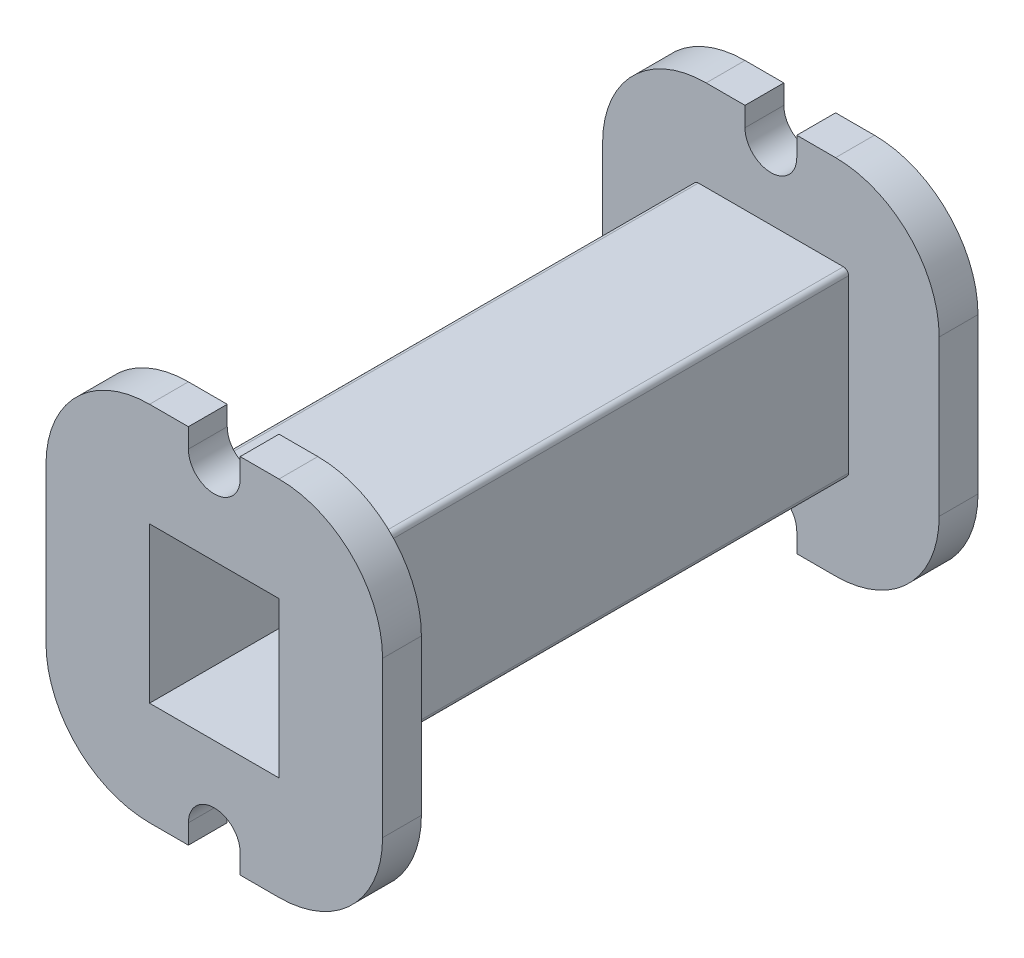
SolidWorks part; units mm, degrees
ref_plane "前视基准面" through (0, 0, 0) normal (0, 0, 1) x (1, 0, 0)
ref_plane "上视基准面" through (0, 0, 0) normal (0, 1, 0) x (1, 0, 0)
ref_plane "右视基准面" through (0, 0, 0) normal (1, 0, 0) x (0, 0, -1)
sketch "草图1" plane through (0, 0, 0) normal (0, 0, 1) x (1, 0, 0)
  line L0 (-3, 3.5) -> (3, 3.5)
  line L1 (-2.5, 3) -> (2.5, 3)
  line L2 (-2.5, 3) -> (-2.5, -3)
  line L3 (-2.5, -3) -> (2.5, -3)
  line L4 (2.5, 3) -> (2.5, -3)
  line L5 (-2.5, 3) -> (2.5, -3) construction
  line L6 (-2.5, -3) -> (2.5, 3) construction
  line L7 (3, 3.5) -> (3, -3.5)
  line L8 (-3, -3.5) -> (3, -3.5)
  line L9 (-3, 3.5) -> (-3, -3.5)
  point P0 (0, 0)
  dimension "D1" = 5
  dimension "D2" = 6
  dimension "D3" = 0.5
extrude "凸台-拉伸1" add sketch "草图1" along normal mid plane 23
sketch "草图2" plane through (0, 0, 11.5) normal (0, 0, 1) x (1, 0, 0)
  line L1 (-3, -3.5) -> (3, -3.5)
  line L2 (-3, -3.5) -> (-3, 3.5)
  line L3 (-3, 3.5) -> (3, 3.5)
  line L4 (3, -3.5) -> (3, 3.5)
  line L5 (-3, -3.5) -> (3, 3.5) construction
  line L6 (-3, 3.5) -> (3, -3.5) construction
  line L7 (-6.5, -10.75) -> (6.5, -10.75)
  line L8 (-6.5, -10.75) -> (-6.5, 10.75)
  line L9 (-6.5, 10.75) -> (6.5, 10.75)
  line L10 (6.5, -10.75) -> (6.5, 10.75)
  line L11 (-6.5, -10.75) -> (6.5, 10.75) construction
  line L12 (-6.5, 10.75) -> (6.5, -10.75) construction
  circle A0 centre (0, 0) radius 9.5
  point P0 (0, 0)
  point P7 (0, 0)
  line M3 (-3, 3.5) -> (-3, -3.5)
  line M4 (-3, -3.5) -> (3, -3.5)
  line M5 (3, -3.5) -> (3, 3.5)
  line M6 (3, 3.5) -> (-3, 3.5)
  dimension "D3" = 19
  dimension "D1" = 13
  dimension "D2" = 21.5
extrude "凸台-拉伸2" add sketch "草图2" against normal blind 1.5 contours L10 A0 L8 M3 M6 M5 M4
mirror "镜向1" about plane through (0, 0, 0) normal (0, 0, 1) of "凸台-拉伸2"
sketch "草图3" plane through (0, 0, 11.5) normal (0, 0, 1) x (1, 0, 0)
  line L1 (-9.3579, 7) -> (9.3579, 7)
  line L2 (-9.3579, 7) -> (-9.3579, -7)
  line L3 (-9.3579, -7) -> (9.3579, -7)
  line L4 (9.3579, 7) -> (9.3579, -7)
  line L5 (-9.3579, 7) -> (9.3579, -7) construction
  line L6 (-9.3579, -7) -> (9.3579, 7) construction
  circle A0 centre (0, 0) radius 19.1004
  point P0 (0, 0)
  dimension "D1" = 14
extrude "切除-拉伸1" cut sketch "草图3" against normal through all
sketch "草图4" plane through (0, 0, 11.5) normal (0, 0, 1) x (1, 0, 0)
  line L4 (-6.4226, -7) -> (6.4226, -7)
  line L5 (6.5, -6.9282) -> (6.5, 6.9282)
  line L6 (6.4226, 7) -> (-6.4226, 7)
  line L7 (-6.5, 6.9282) -> (-6.5, -6.9282)
  line L8 (-6.4226, -7) -> (6.4226, -7)
  line L9 (6.5, -6.9282) -> (6.5, 6.9282)
  line L10 (6.4226, 7) -> (-6.4226, 7)
  line L11 (-6.5, 6.9282) -> (-6.5, -6.9282)
  circle A0 centre (-2.5, 3) radius 4
  circle A1 centre (2.5, 3) radius 4
  circle A2 centre (2.5, -3) radius 4
  circle A3 centre (-2.5, -3) radius 4
  arc A8 (-6.5, -6.9282) -> (-6.4226, -7) centre (0, 0) ccw
  arc A9 (6.4226, -7) -> (6.5, -6.9282) centre (0, 0) ccw
  arc A10 (6.5, 6.9282) -> (6.4226, 7) centre (0, 0) ccw
  arc A11 (-6.4226, 7) -> (-6.5, 6.9282) centre (0, 0) ccw
  arc A12 (-6.5, -6.9282) -> (-6.4226, -7) centre (0, 0) ccw
  arc A13 (6.4226, -7) -> (6.5, -6.9282) centre (0, 0) ccw
  arc A14 (6.5, 6.9282) -> (6.4226, 7) centre (0, 0) ccw
  arc A15 (-6.4226, 7) -> (-6.5, 6.9282) centre (0, 0) ccw
  arc M17 (-6.5, -6.9282) -> (-6.4226, -7) centre (0, 0) ccw
  line M18 (-6.4226, -7) -> (6.4226, -7)
  arc M19 (6.4226, -7) -> (6.5, -6.9282) centre (0, 0) ccw
  line M20 (6.5, -6.9282) -> (6.5, 6.9282)
  arc M21 (6.5, 6.9282) -> (6.4226, 7) centre (0, 0) ccw
  line M22 (6.4226, 7) -> (-6.4226, 7)
  arc M23 (-6.4226, 7) -> (-6.5, 6.9282) centre (0, 0) ccw
  line M24 (-6.5, 6.9282) -> (-6.5, -6.9282)
  dimension "D1" = 0
extrude "切除-拉伸2" cut sketch "草图4" against normal through all contours A0 L10 M23 M24 | A1 L9 M21 M22 | A2 L8 M19 M20 | A3 M24 M17 M18
sketch "草图5" plane through (0, 0, 11.5) normal (0, 0, 1) x (1, 0, 0)
  line L0 (0, 7.75) -> (0, 6.25) construction
  line L1 (-6.2, 12.6435) -> (6.2, 12.6435)
  line L2 (-6.2, 12.6435) -> (-6.2, -12.6435)
  line L3 (-6.2, -12.6435) -> (6.2, -12.6435)
  line L4 (6.2, 12.6435) -> (6.2, -12.6435)
  line L5 (-6.2, 12.6435) -> (6.2, -12.6435) construction
  line L6 (-6.2, -12.6435) -> (6.2, 12.6435) construction
  line L7 (2.5, 7) -> (-2.5, 7) construction
  line L8 (1, 7.75) -> (1, 6.25)
  line L9 (-1, 7.75) -> (-1, 6.25)
  line L10 (0, -6.25) -> (0, -7.75) construction
  line L11 (-2.5, -7) -> (2.5, -7) construction
  line L12 (1, -6.25) -> (1, -7.75)
  line L13 (-1, -6.25) -> (-1, -7.75)
  line L14 (6.5, -3) -> (6.5, 3) construction
  line L16 (-13.2201, 15.7714) -> (13.2201, 15.7714)
  line L17 (-13.2201, 15.7714) -> (-13.2201, -15.7714)
  line L18 (-13.2201, -15.7714) -> (13.2201, -15.7714)
  line L19 (13.2201, 15.7714) -> (13.2201, -15.7714)
  line L20 (-13.2201, 15.7714) -> (13.2201, -15.7714) construction
  line L21 (-13.2201, -15.7714) -> (13.2201, 15.7714) construction
  arc A0 (1, 7.75) -> (-1, 7.75) centre (0, 7.75) ccw
  arc A1 (-1, 6.25) -> (1, 6.25) centre (0, 6.25) ccw
  arc A2 (1, -6.25) -> (-1, -6.25) centre (0, -6.25) ccw
  arc A3 (-1, -7.75) -> (1, -7.75) centre (0, -7.75) ccw
  point P0 (0, 0)
  point P10 (0, 7)
  point P16 (0, -7)
  point P26 (0, 0)
  line M13 (-2.5, -7) -> (2.5, -7)
  line M17 (2.5, 7) -> (-2.5, 7)
  dimension "D1" = 1
  dimension "D2" = 1
  dimension "D3" = 1.5
  dimension "D4" = 1.5
  dimension "D5" = 0.3
extrude "切除-拉伸3" cut sketch "草图5" against normal through all both and the other way through all contours L9 A1 L8 M17 | L12 A2 L13 M13
fillet "圆角1" radius 0.2 4 edges at (3, 3.5, 0) (-3, -3.5, 0) (-3, 3.5, 0) (3, -3.5, 0)
